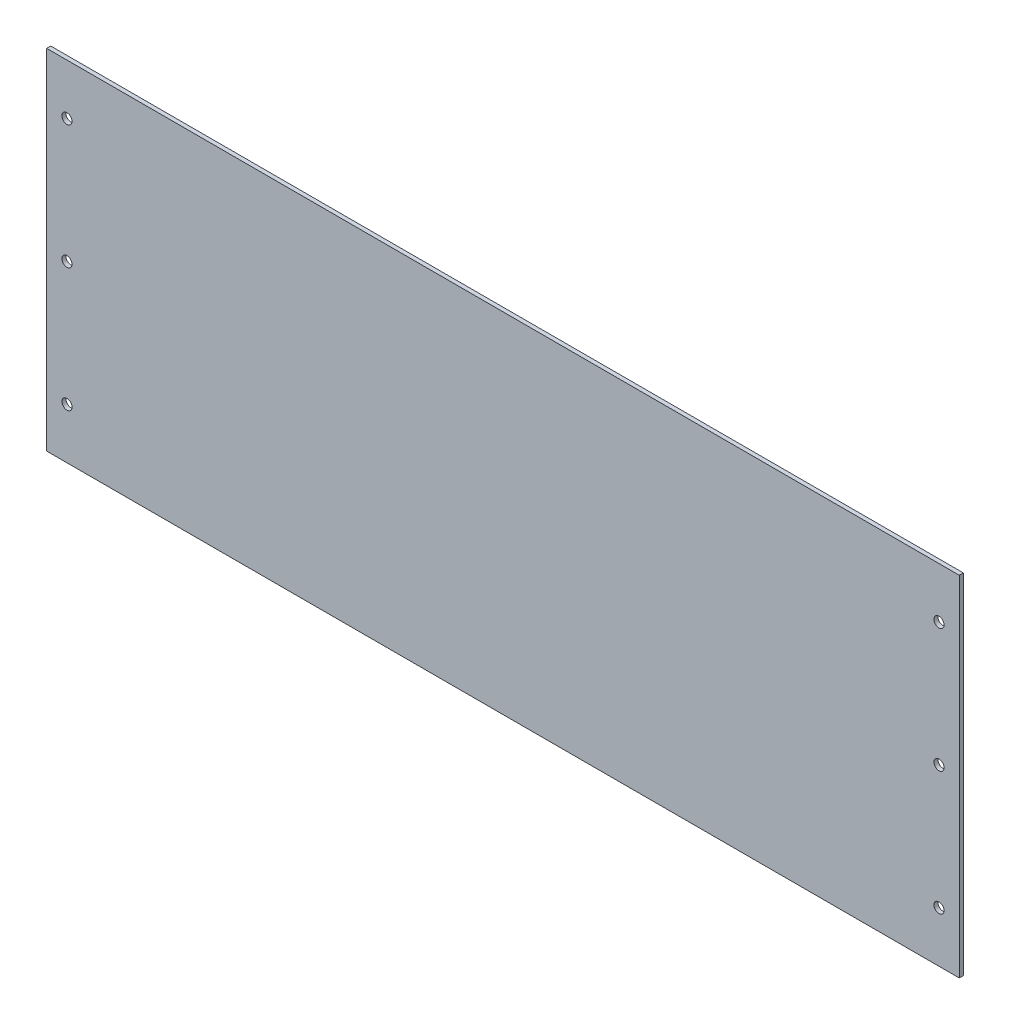
SolidWorks part; units mm, degrees
material "1345 Alloy"
ref_plane "Front Plane" through (0, 0, 0) normal (0, 0, 1) x (1, 0, 0)
ref_plane "Top Plane" through (0, 0, 0) normal (0, 1, 0) x (1, 0, 0)
ref_plane "Right Plane" through (0, 0, 0) normal (1, 0, 0) x (0, 0, -1)
sketch "Sketch1" plane through (0, 0, 0) normal (0, 0, 1) x (1, 0, 0)
  line L1 (-225, 86) -> (225, 86)
  line L2 (-225, 86) -> (-225, -86)
  line L3 (-225, -86) -> (225, -86)
  line L4 (225, 86) -> (225, -86)
  line L5 (-225, 86) -> (225, -86) construction
  line L6 (-225, -86) -> (225, 86) construction
  point P0 (0, 0)
  dimension "D1" = 450
  dimension "D2" = 172
extrude "Boss-Extrude1" add sketch "Sketch1" along normal blind 2
sketch "Sketch2" plane through (0, 0, 2) normal (0, 0, 1) x (1, 0, 0)
  line L0 (-215, 61) -> (-215, -61) construction
  line L5 (215, -61) -> (-215, 61) construction
  line L6 (215, 61) -> (-215, -61) construction
  circle A0 centre (-215, 61) radius 2.5
  circle A1 centre (215, 61) radius 2.5
  circle A2 centre (215, -61) radius 2.5
  circle A3 centre (-215, -61) radius 2.5
  circle A4 centre (-215, 0) radius 2.5
  circle A5 centre (215, 0) radius 2.5
  point P0 (0, 0)
  dimension "D3" = 5
  dimension "D6" = 5
  dimension "D8" = 5
  dimension "D9" = 5
  dimension "D10" = 5
  dimension "D11" = 5
  dimension "D1" = 430
  dimension "D2" = 122
  dimension "D7" = 2
  dimension "D4" = 2
  dimension "D5" = 2
extrude "Cut-Extrude1" cut sketch "Sketch2" against normal through all
